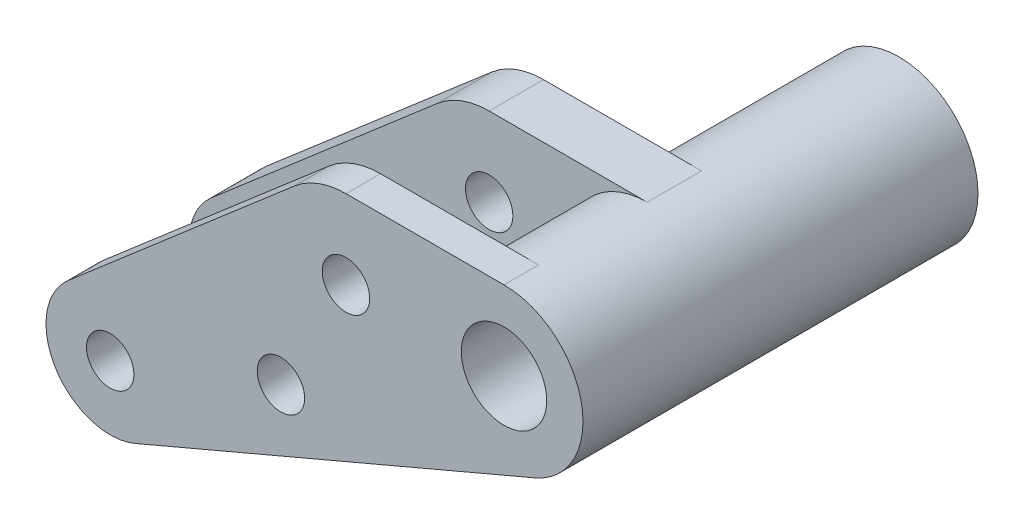
SolidWorks part; units mm, degrees
ref_plane "Front Plane" through (0, 0, 0) normal (0, 0, 1) x (1, 0, 0)
ref_plane "Top Plane" through (0, 0, 0) normal (0, 1, 0) x (1, 0, 0)
ref_plane "Right Plane" through (0, 0, 0) normal (1, 0, 0) x (0, 0, -1)
sketch "Sketch1" plane through (0, 0, 0) normal (0, 0, 1) x (1, 0, 0)
  line L0 (-12.7, 0) -> (0, 0) construction
  line L3 (-31.6528, -14.7599) -> (0, 0) construction
  line L6 (-29.633, -19.5075) -> (2.4859, -5.8432)
  line L7 (0, 0) -> (-31.6528, -14.7599) construction
  line L8 (-35.0207, -10.8515) -> (-16.8451, 4.8104)
  line L9 (-12.7, 6.35) -> (0, 6.35)
  arc A0 (2.4859, -5.8432) -> (0, 6.35) centre (0, 0) ccw
  arc A3 (-35.0207, -10.8515) -> (-29.633, -19.5075) centre (-31.6528, -14.7599) ccw
  circle A4 centre (-12.7, 0) radius 1.905
  circle A5 centre (-31.6528, -14.7599) radius 1.905
  circle A6 centre (0, 0) radius 3.429
  arc A8 (-12.7, 6.35) -> (-16.8451, 4.8104) centre (-12.7, 0) ccw
  dimension "D3" = 3.81
  dimension "D4" = 10.3187
  dimension "D5" = 6.35
  dimension "D6" = 6.35
  dimension "D8" = 3.81
  dimension "D9" = 6.858
  dimension "D1" = 12.7
  dimension "D2" = 34.925
  dimension "D7" = 25
extrude "Boss-Extrude1" add sketch "Sketch1" against normal blind 15.875
sketch "Sketch5" plane through (0, 0, 0) normal (0, 0, 1) x (1, 0, 0)
  line L0 (-16.8451, 4.8104) -> (-35.0207, -10.8515) construction
  line L1 (-29.633, -19.5075) -> (2.4859, -5.8432) construction
  line L2 (-26.4934, -3.5035) -> (-35.0207, -10.8515)
  line L3 (-29.633, -19.5075) -> (-26.4934, -18.1719)
  line L4 (-26.4934, -18.1719) -> (-26.4934, -3.5035)
  arc A0 (-35.0207, -10.8515) -> (-29.633, -19.5075) centre (-31.6528, -14.7599) ccw construction
  arc A1 (-35.0207, -10.8515) -> (-29.633, -19.5075) centre (-31.6528, -14.7599) ccw
  circle A2 centre (-31.6528, -14.7599) radius 5.1594 construction
extrude "Cut-Extrude3" [suppressed] cut sketch "Sketch5" against normal blind 9.525
ref_plane "Plane1" through (0, 0, -7.1437) normal (0, 0, 1) x (1, 0, 0)
sketch "Sketch4" plane through (0, 0, -7.1437) normal (0, 0, 1) x (1, 0, 0)
  line L7 (0, 6.35) -> (-12.7, 6.35) construction
  line L8 (-16.8451, 4.8104) -> (-35.0207, -10.8515) construction
  line L10 (0, 6.35) -> (-12.7, 6.35)
  line L11 (-16.8451, 4.8104) -> (-35.0207, -10.8515)
  line L12 (-15.074, -5.8895) -> (-20.2858, -3.7888)
  line L14 (-27.0539, -17.0985) -> (-20.2858, -3.7888)
  line L15 (-29.633, -19.5075) -> (2.4859, -5.8432) construction
  arc A8 (-35.0207, -10.8515) -> (-29.633, -19.5075) centre (-31.6528, -14.7599) ccw construction
  arc A12 (-35.0207, -10.8515) -> (-29.633, -19.5075) centre (-31.6528, -14.7599) ccw
  arc A13 (0, 6.35) -> (-6.35, 0) centre (0, 0) ccw
  arc A16 (-15.074, -5.8895) -> (-6.35, 0) centre (-12.7, 0) ccw
  arc A17 (-12.7, 6.35) -> (-16.8451, 4.8104) centre (-12.7, 0) ccw construction
  arc A18 (-12.7, 6.35) -> (-16.8451, 4.8104) centre (-12.7, 0) ccw
  arc A19 (-29.633, -19.5075) -> (-27.0539, -17.0985) centre (-31.6528, -14.7599) ccw
  dimension "D1" = 6.35
  dimension "D2" = 40
  dimension "D3" = 95
extrude "Cut-Extrude2" cut sketch "Sketch4" against normal mid plane 8.7312
sketch "Sketch6" plane through (0, 0, -15.875) normal (0, 0, -1) x (-1, 0, 0)
  circle A0 centre (0, 0) radius 6.35
  circle A1 centre (0, 0) radius 3.429 construction
  circle A2 centre (0, 0) radius 3.429
  arc A3 (0, 6.35) -> (-2.4859, -5.8432) centre (0, 0) ccw construction
extrude "Boss-Extrude2" add sketch "Sketch6" along normal offset from surface (15.875 mm away) 31.75 up to face at (3.429, 0, 0)
sketch "Sketch7" plane through (0, 0, -15.875) normal (0, 0, -1) x (-1, 0, 0)
  line L0 (29.633, -19.5075) -> (-2.4859, -5.8432) construction
  circle A0 centre (17.9305, -9.5604) radius 1.905
  dimension "D1" = 3.81
  dimension "D2" = 4.572
  dimension "D3" = 20.32
extrude "Cut-Extrude4" cut sketch "Sketch7" against normal through all
sketch "Sketch8" plane through (0, 0, -15.875) normal (0, 0, -1) x (-1, 0, 0)
  circle A0 centre (17.9305, -9.5604) radius 2.286
  dimension "D1" = 4.572
extrude "Cut-Extrude5" cut sketch "Sketch8" against normal up to surface (4.3656 mm away) up to face at (-18.4827, -4.7545, -11.5094)
